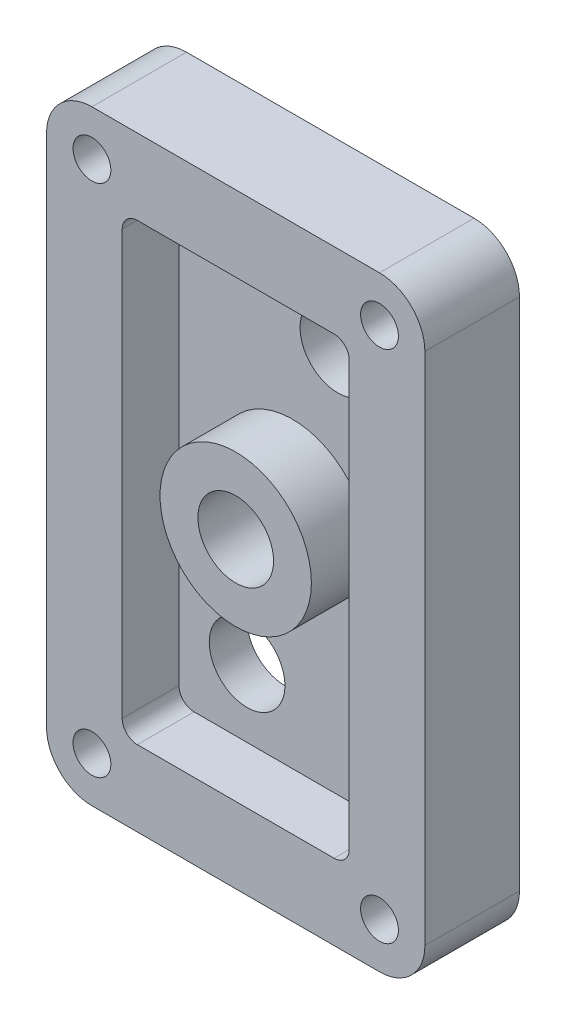
SolidWorks part; units mm, degrees
material "Alliage 1060"
ref_plane "Plan de face" through (0, 0, 0) normal (0, 0, 1) x (1, 0, 0)
ref_plane "Plan de dessus" through (0, 0, 0) normal (0, 1, 0) x (1, 0, 0)
ref_plane "Plan de droite" through (0, 0, 0) normal (1, 0, 0) x (0, 0, -1)
sketch "Esquisse1" plane through (0, 0, 0) normal (0, 0, 1) x (1, 0, 0)
  line L0 (500, -102.2574) -> (500, 1350.1696) construction
  line L1 (0, 0) -> (1000, 0)
  line L2 (0, 0) -> (0, 1600)
  line L3 (0, 1600) -> (1000, 1600)
  line L4 (1000, 0) -> (1000, 1600)
  line L5 (200, 200) -> (800, 200)
  line L6 (200, 200) -> (200, 1400)
  line L7 (200, 1400) -> (800, 1400)
  line L8 (800, 200) -> (800, 1400)
  line L9 (-97.6838, 800) -> (1151.7065, 800) construction
  circle A0 centre (500, 800) radius 100
  circle A1 centre (500, 800) radius 200
  circle A2 centre (380, 380) radius 100
  circle A3 centre (120, 1480) radius 50
  circle A4 centre (880, 1480) radius 50
  circle A5 centre (880, 120) radius 50
  circle A6 centre (120, 120) radius 50
  circle A8 centre (620, 1220) radius 100
  dimension "D13" = 100
  dimension "D16" = 400
  dimension "D17" = 200
  dimension "D18" = 200
  dimension "D19" = 200
  dimension "D1" = 1000
  dimension "D2" = 1600
  dimension "D3" = 1200
  dimension "D4" = 600
  dimension "D5" = 200
  dimension "D6" = 200
  dimension "D7" = 240
  dimension "D8" = 120
  dimension "D9" = 840
  dimension "D10" = 380
  dimension "D11" = 760
  dimension "D12" = 500
  dimension "D14" = 120
  dimension "D15" = 800
  dimension "D20" = 380
extrude "Boss.-Extru.1" add sketch "Esquisse1" along normal blind 250 contours L1 L4 L3 L2 A4 A3 L8 L5 L6 L7 A5 A6 | A1 A0 | L5 L8 L7 L6 A8 A2 A1
sketch "Esquisse3" plane through (0, 0, 250) normal (0, 0, 1) x (1, 0, 0)
  line L0 (0, 0) -> (1000, 0) construction
  line L1 (240, 1400) -> (760, 1400)
  line L2 (200, 1360) -> (200, 240)
  line L3 (240, 200) -> (760, 200)
  line L4 (800, 1360) -> (800, 240)
  line L5 (0, 0) -> (0, 1600) construction
  circle A0 centre (500, 800) radius 200
  circle A2 centre (500, 800) radius 100 construction
  arc A3 (200, 1360) -> (240, 1400) centre (240, 1360) cw
  arc A4 (760, 200) -> (800, 240) centre (760, 240) ccw
  arc A5 (200, 240) -> (240, 200) centre (240, 240) ccw
  arc A6 (800, 1360) -> (760, 1400) centre (760, 1360) ccw
  dimension "D1" = 40
  dimension "D2" = 40
  dimension "D3" = 400
  dimension "D4" = 1200
  dimension "D5" = 600
  dimension "D6" = 200
  dimension "D7" = 200
extrude "Enlèv. mat.-Extru.1" cut sketch "Esquisse3" against normal blind 150
fillet "Congé1" radius 120 4 edges at (0, 0, 125) (1000, 0, 125) (0, 1600, 125) (1000, 1600, 125)
